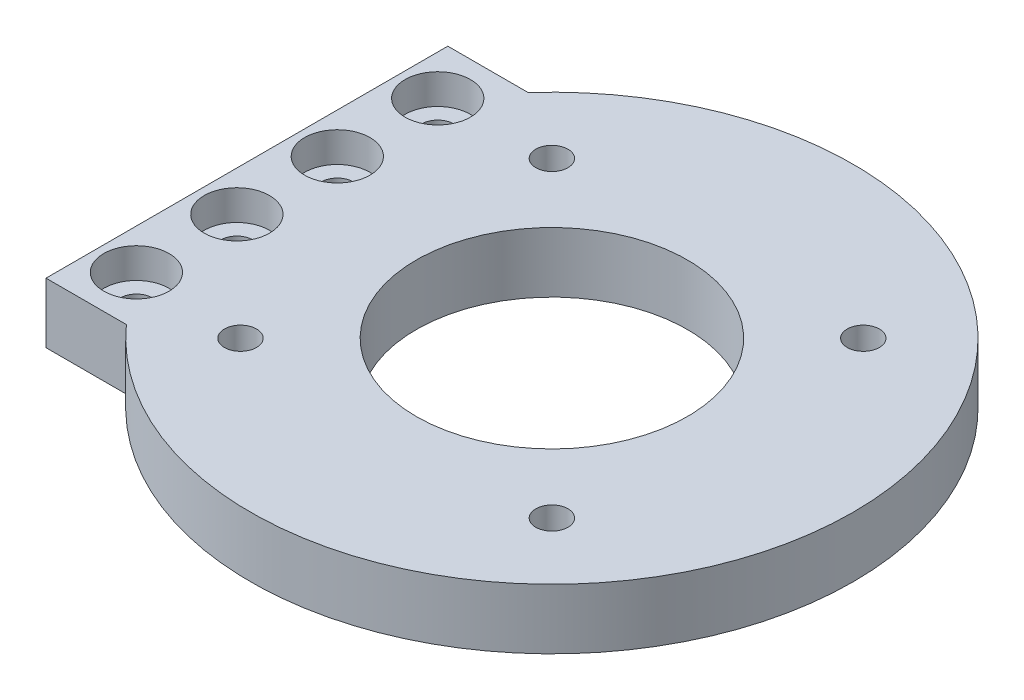
SolidWorks part; units mm, degrees
ref_plane "前视基准面" through (0, 0, 0) normal (0, 0, 1) x (1, 0, 0)
ref_plane "上视基准面" through (0, 0, 0) normal (0, 1, 0) x (1, 0, 0)
ref_plane "右视基准面" through (0, 0, 0) normal (1, 0, 0) x (0, 0, -1)
other "Configuration Table"
sketch "草图1" plane through (0, 0, 0) normal (0, 1, 0) x (1, 0, 0)
  line L3 (0, 90) -> (30, 90)
  line L5 (15, 90) -> (50015, 90) construction
  line L9 (15, 90) -> (35370.3391, 35445.3391) construction
  line L10 (15, 90) -> (35370.3391, -35265.3391) construction
  circle A0 centre (15, 90) radius 30
  circle A1 centre (30.5, 105.5) radius 1.6
  circle A2 centre (-0.5, 105.5) radius 1.6
  circle A5 centre (15, 90) radius 13.5
  circle A8 centre (15, 90) radius 17.5 construction
  circle A13 centre (30.5, 74.5) radius 1.6
  circle A14 centre (-0.5, 74.5) radius 1.6
  dimension "D3" = 60
  dimension "D5" = 15.5
  dimension "D6" = 3.2
  dimension "D7" = 27
  dimension "D9" = 35
extrude "凸台-拉伸1" add sketch "草图1" along normal blind 6
sketch "草图2" plane through (0, 6, 0) normal (0, 1, 0) x (1, 0, 0)
  line L0 (15, 90) -> (50015, 90) construction
  line L1 (-7.3607, 70) -> (-15.3607, 70)
  line L2 (-7.3607, 70) -> (-7.3607, 110)
  line L3 (-7.3607, 110) -> (-15.3607, 110)
  line L4 (-15.3607, 70) -> (-15.3607, 110)
  line L5 (15, 90) -> (15, 50090) construction
  line L7 (-5.9519, 111) -> (36.0481, 111) construction
  line L8 (-5.9519, 111) -> (-5.9519, 69) construction
  line L9 (-5.9519, 69) -> (36.0481, 69) construction
  line L10 (36.0481, 111) -> (36.0481, 69) construction
  line L11 (-5.9519, 111) -> (36.0481, 69) construction
  line L12 (-5.9519, 69) -> (36.0481, 111) construction
  circle A0 centre (15, 90) radius 30 construction
  point P10 (15.0481, 90)
  dimension "D1" = 40
  dimension "D2" = 20
  dimension "D3" = 42
  dimension "D4" = 42
  dimension "D5" = 8
extrude "凸台-拉伸2" add sketch "草图2" against normal blind 6
sketch "草图3" plane through (0, 6, 0) normal (0, 1, 0) x (1, 0, 0)
  line L2 (-7.3607, 110) -> (-15.3607, 110) construction
  line L3 (-15.3607, 110) -> (-15.3607, 70) construction
  circle A0 centre (-11.3607, 105) radius 1.6
  circle A1 centre (-11.3607, 95) radius 1.6
  circle A2 centre (-11.3607, 85) radius 1.6
  circle A3 centre (-11.3607, 75) radius 1.6
  dimension "D2" = 4
  dimension "D3" = 3.2
  dimension "D4" = 4
  dimension "D1" = 5
extrude "切除-拉伸1" cut sketch "草图3" against normal blind 6
sketch "草图4" plane through (0, 6, 0) normal (0, 1, 0) x (1, 0, 0)
  circle A0 centre (-11.3607, 105) radius 3.25
  circle A1 centre (-11.3607, 95) radius 3.25
  circle A2 centre (-11.3607, 85) radius 3.25
  circle A3 centre (-11.3607, 75) radius 3.25
  dimension "D1" = 6.5
  dimension "D2" = 4
extrude "切除-拉伸2" cut sketch "草图4" against normal blind 3
